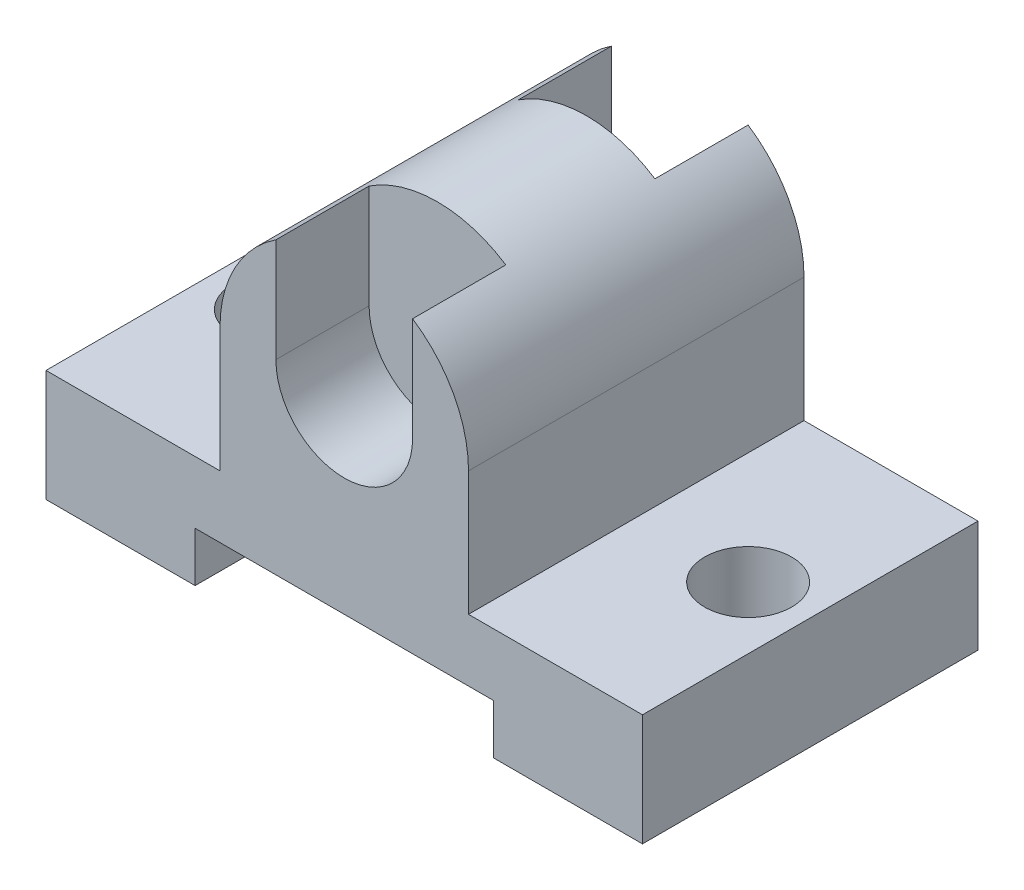
SolidWorks part; units mm, degrees
ref_plane "Front Plane" through (0, 0, 0) normal (0, 0, 1) x (1, 0, 0)
ref_plane "Top Plane" through (0, 0, 0) normal (0, 1, 0) x (1, 0, 0)
ref_plane "Right Plane" through (0, 0, 0) normal (1, 0, 0) x (0, 0, -1)
sketch "Sketch1" plane through (0, 0, 0) normal (0, 0, 1) x (1, 0, 0)
  line L0 (-48.7915, 0) -> (-24.7915, 0)
  line L1 (-48.7915, 0) -> (-48.7915, 18)
  line L2 (-48.7915, 18) -> (-20.7915, 18)
  line L3 (-20.7915, 18) -> (-20.7915, 38)
  line L4 (-24.7915, 0) -> (-24.7915, 8)
  line L5 (-24.7915, 8) -> (23.2085, 8)
  line L6 (23.2085, 8) -> (23.2085, 0)
  line L7 (23.2085, 0) -> (47.2085, 0)
  line L8 (47.2085, 0) -> (47.2085, 18)
  line L9 (47.2085, 18) -> (19.2085, 18)
  line L10 (19.2085, 18) -> (19.2085, 38)
  arc A2 (-20.7915, 38) -> (19.2085, 38) centre (-0.7915, 38) cw
  dimension "D9" = 20
  dimension "D1" = 96
  dimension "D2" = 48
  dimension "D3" = 8
  dimension "D4" = 18
  dimension "D5" = 18
  dimension "D6" = 20
  dimension "D7" = 20
extrude "Boss-Extrude1" add sketch "Sketch1" against normal blind 54
sketch "Sketch2" plane through (0, 18, 0) normal (0, 1, 0) x (1, 0, 0)
  line L0 (47.2085, 54) -> (47.2085, 0) construction
  line L1 (47.2085, 0) -> (19.2085, 0) construction
  line L2 (-48.7915, 54) -> (-48.7915, 0) construction
  circle A0 centre (37.2085, 27) radius 7
  circle A1 centre (-38.7915, 27) radius 7
  point P8 (40.0719, 36.4658)
  dimension "D1" = 10
  dimension "D2" = 27
  dimension "D3" = 10
extrude "Cut-Extrude1" cut sketch "Sketch2" against normal blind 54
sketch "Sketch3" plane through (0, 0, 0) normal (0, 0, 1) x (1, 0, 0)
  line L0 (-0.7915, 58) -> (-0.7915, 38)
  line L1 (-0.7915, 58) -> (-0.7915, 38) construction
  line L2 (10.2085, 58) -> (10.2085, 38)
  line L3 (-11.7915, 58) -> (-11.7915, 38)
  arc A0 (19.2085, 38) -> (-20.7915, 38) centre (-0.7915, 38) ccw construction
  arc A1 (10.2085, 58) -> (-11.7915, 58) centre (-0.7915, 58) ccw
  arc A2 (-11.7915, 38) -> (10.2085, 38) centre (-0.7915, 38) ccw
  point P6 (-0.7915, 48)
  dimension "D1" = 11
extrude "Cut-Extrude2" cut sketch "Sketch3" against normal blind 15
sketch "Sketch4" plane through (0, 0, -54) normal (0, 0, -1) x (-1, 0, 0)
  line L0 (0.7915, 58) -> (0.7915, 38) construction
  line L1 (11.7915, 58) -> (11.7915, 38)
  line L2 (-10.2085, 58) -> (-10.2085, 38)
  arc A0 (20.7915, 38) -> (-19.2085, 38) centre (0.7915, 38) ccw construction
  arc A1 (11.7915, 58) -> (-10.2085, 58) centre (0.7915, 58) ccw
  arc A2 (-10.2085, 38) -> (11.7915, 38) centre (0.7915, 38) ccw
  point P6 (0.7915, 48)
  dimension "D1" = 11
extrude "Cut-Extrude3" cut sketch "Sketch4" against normal blind 15
